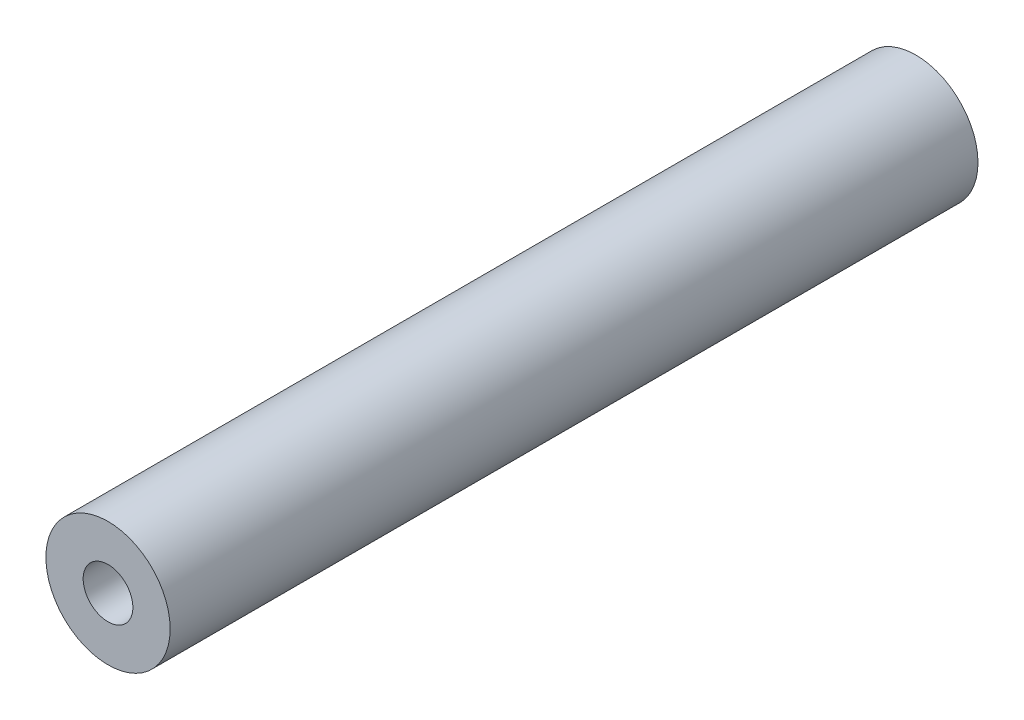
SolidWorks part; units mm, degrees
ref_plane "Plano frontal" through (0, 0, 0) normal (0, 0, 1) x (1, 0, 0)
ref_plane "Plano superior" through (0, 0, 0) normal (0, 1, 0) x (1, 0, 0)
ref_plane "Plano direito" through (0, 0, 0) normal (1, 0, 0) x (0, 0, -1)
sketch "Esboço1" plane through (0, 0, 0) normal (0, 0, 1) x (1, 0, 0)
  circle A0 centre (0, 0) radius 5
  circle A1 centre (0, 0) radius 2
  dimension "D1" = 10
  dimension "D2" = 4
extrude "Ressalto-extrusão1" add sketch "Esboço1" along normal blind 65
